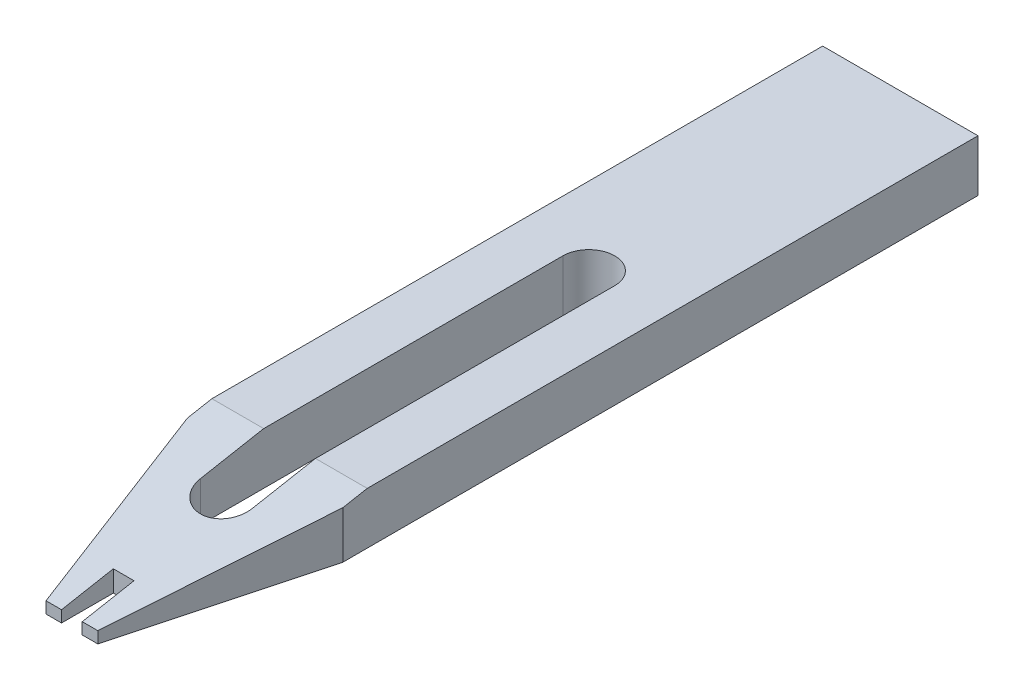
SolidWorks part; units mm, degrees
ref_plane "Front Plane" through (0, 0, 0) normal (0, 0, 1) x (1, 0, 0)
ref_plane "Top Plane" through (0, 0, 0) normal (0, 1, 0) x (1, 0, 0)
ref_plane "Right Plane" through (0, 0, 0) normal (1, 0, 0) x (0, 0, -1)
sketch "Sketch1" plane through (0, 0, 0) normal (0, 1, 0) x (1, 0, 0)
  line L0 (0, -25.0788) -> (0, 9.9212) construction
  line L1 (-7.5, 40) -> (7.5, 40)
  line L2 (-7.5, 40) -> (-7.5, -40)
  line L3 (-1, -40) -> (-7.5, -40)
  line L4 (7.5, 40) -> (7.5, -40)
  line L5 (-7.5, 40) -> (7.5, -40) construction
  line L6 (-7.5, -40) -> (7.5, 40) construction
  line L7 (-2.5, -25.0788) -> (-2.5, 9.9212)
  line L8 (2.5, -25.0788) -> (2.5, 9.9212)
  line L9 (-1, -40) -> (-1, -35)
  line L10 (-1, -35) -> (1, -35)
  line L11 (1, -35) -> (1, -40)
  line L12 (1, -40) -> (7.5, -40)
  arc A0 (-2.5, -25.0788) -> (2.5, -25.0788) centre (0, -25.0788) ccw
  arc A1 (2.5, 9.9212) -> (-2.5, 9.9212) centre (0, 9.9212) ccw
  point P0 (0, 0)
  point P8 (0, -7.5788)
  dimension "D3" = 35
  dimension "D5" = 2
  dimension "D1" = 80
  dimension "D2" = 15
  dimension "D4" = 5
  dimension "D6" = 6.5
  dimension "D7" = 5
extrude "Boss-Extrude1" add sketch "Sketch1" along normal blind 5
chamfer "Chamfer1" distance 5 angle 75 2 edges at (-7.5, 2.5, 40) (7.5, 2.5, 40)
sketch "Sketch2" plane through (0, 0, 0) normal (1, 0, 0) x (0, 0, -1)
  line L0 (-42.1953, 0.7063) -> (-15.1437, 5.7094)
  line L1 (-15.1437, 5.7094) -> (-42.1953, 5.7094)
  line L2 (-42.1953, 5.7094) -> (-42.1953, 0.7063)
extrude "Cut-Extrude1" cut sketch "Sketch2" against normal blind 10 and the other way blind 10
